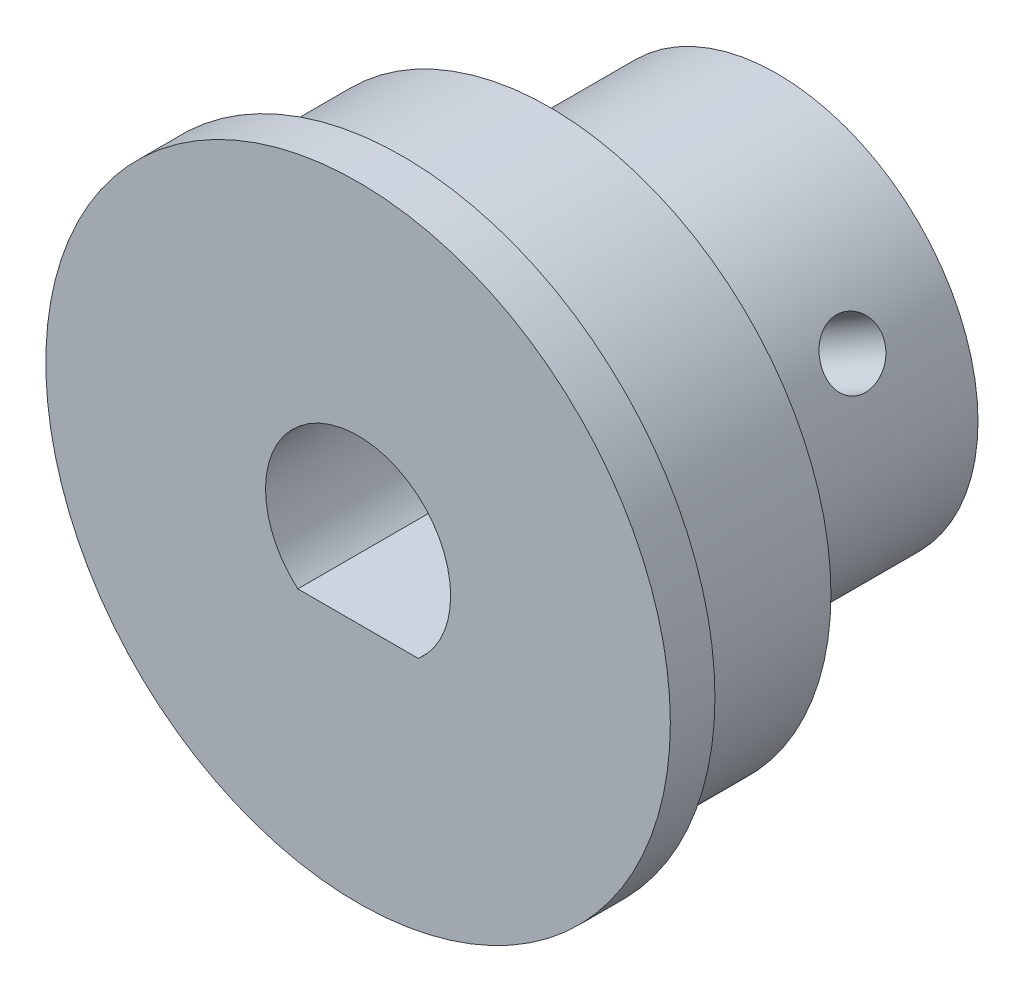
SolidWorks part; units mm, degrees
ref_plane "前视基准面" through (0, 0, 0) normal (0, 0, 1) x (1, 0, 0)
ref_plane "上视基准面" through (0, 0, 0) normal (0, 1, 0) x (1, 0, 0)
ref_plane "右视基准面" through (0, 0, 0) normal (1, 0, 0) x (0, 0, -1)
sketch "草图1" plane through (0, 0, 0) normal (0, 0, 1) x (1, 0, 0)
  circle A0 centre (0, 0) radius 12.6
  dimension "D1" = 25.2
extrude "凸台-拉伸1" add sketch "草图1" along normal blind 6.6
sketch "草图2" plane through (0, 0, 6.6) normal (0, 0, 1) x (1, 0, 0)
  circle A0 centre (0, 0) radius 14
  dimension "D1" = 28
extrude "凸台-拉伸2" add sketch "草图2" along normal blind 2
sketch "草图4" plane through (0, 0, 0) normal (0, 0, -1) x (-1, 0, 0)
  circle A0 centre (-0.1932, 0) radius 9
  dimension "D1" = 18
extrude "凸台-拉伸3" add sketch "草图4" along normal blind 10
sketch "草图5" plane through (0, 0, 0) normal (0, 1, 0) x (1, 0, 0)
  line L0 (0, 0) -> (0, 5.5) construction
  line L1 (12.6, 0) -> (-12.6, 0) construction
  circle A0 centre (0, 5.5) radius 1.35
  dimension "D1" = 2.7
  dimension "D2" = 5.5
extrude "切除-拉伸2" cut sketch "草图5" against normal blind 8 from offset 4 offset against normal yes
sketch "草图3" plane through (0, 0, 8.6) normal (0, 0, 1) x (1, 0, 0)
  line L0 (0, 0) -> (0, 4.15) construction
  line L1 (0, 0) -> (4.15, 0) construction
  line L2 (2.7019, 3.15) -> (-2.7019, 3.15)
  line L3 (2.7019, -3.15) -> (-2.7019, -3.15)
  circle A0 centre (0, 0) radius 4.15
  dimension "D1" = 8.3
  dimension "D2" = 3.15
extrude "切除-拉伸1" cut sketch "草图3" against normal through all
pattern_circular "阵列(圆周)1" count 3 over 360 about axis through (0.1932, 0, 0) along (0, 0, 1) of "切除-拉伸2"
